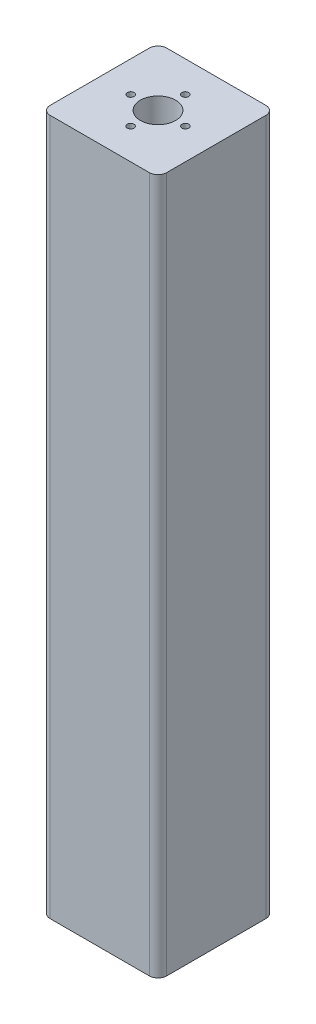
SolidWorks part; units mm, degrees
ref_plane "Front Plane" through (0, 0, 0) normal (0, 0, 1) x (1, 0, 0)
ref_plane "Top Plane" through (0, 0, 0) normal (0, 1, 0) x (1, 0, 0)
ref_plane "Right Plane" through (0, 0, 0) normal (1, 0, 0) x (0, 0, -1)
sketch "Sketch1" plane through (0, 0, 0) normal (0, 1, 0) x (1, 0, 0)
  line L1 (17.018, 17.018) -> (-17.018, 17.018)
  line L2 (17.018, 17.018) -> (17.018, -17.018)
  line L3 (17.018, -17.018) -> (-17.018, -17.018)
  line L4 (-17.018, 17.018) -> (-17.018, -17.018)
  line L5 (17.018, 17.018) -> (-17.018, -17.018) construction
  line L6 (17.018, -17.018) -> (-17.018, 17.018) construction
  point P0 (0, 0)
  dimension "D1" = 34.036
  dimension "D2" = 34.036
extrude "Boss-Extrude1" add sketch "Sketch1" along normal blind 203.2
sketch "Sketch2" plane through (0, 203.2, 0) normal (0, 1, 0) x (1, 0, 0)
  line L0 (0, -8) -> (0, 8) construction
  line L1 (8, 0) -> (-8, 0) construction
  circle A0 centre (0, 0) radius 8 construction
  circle A1 centre (0, 8) radius 1
  circle A2 centre (0, -8) radius 1
  circle A3 centre (-8, 0) radius 1
  circle A4 centre (8, 0) radius 1
  dimension "D1" = 16
  dimension "D2" = 2
extrude "Cut-Extrude1" cut sketch "Sketch2" against normal blind 38.1
fillet "Fillet1" radius 2.54 4 edges at (17.018, 101.6, -17.018) (-17.018, 101.6, -17.018) (17.018, 101.6, 17.018) (-17.018, 101.6, 17.018)
sketch "Sketch3" plane through (0, 203.2, 0) normal (0, 1, 0) x (1, 0, 0)
  circle A0 centre (0, 0) radius 5.15
  dimension "D1" = 10.3
extrude "Cut-Extrude2" cut sketch "Sketch3" against normal blind 190.5
sketch "Sketch4" plane through (0, 0, 0) normal (0, -1, 0) x (1, 0, 0)
  circle A0 centre (0, 0) radius 1.5875
  dimension "D1" = 3.175
extrude "Cut-Extrude3" cut sketch "Sketch4" against normal through all
